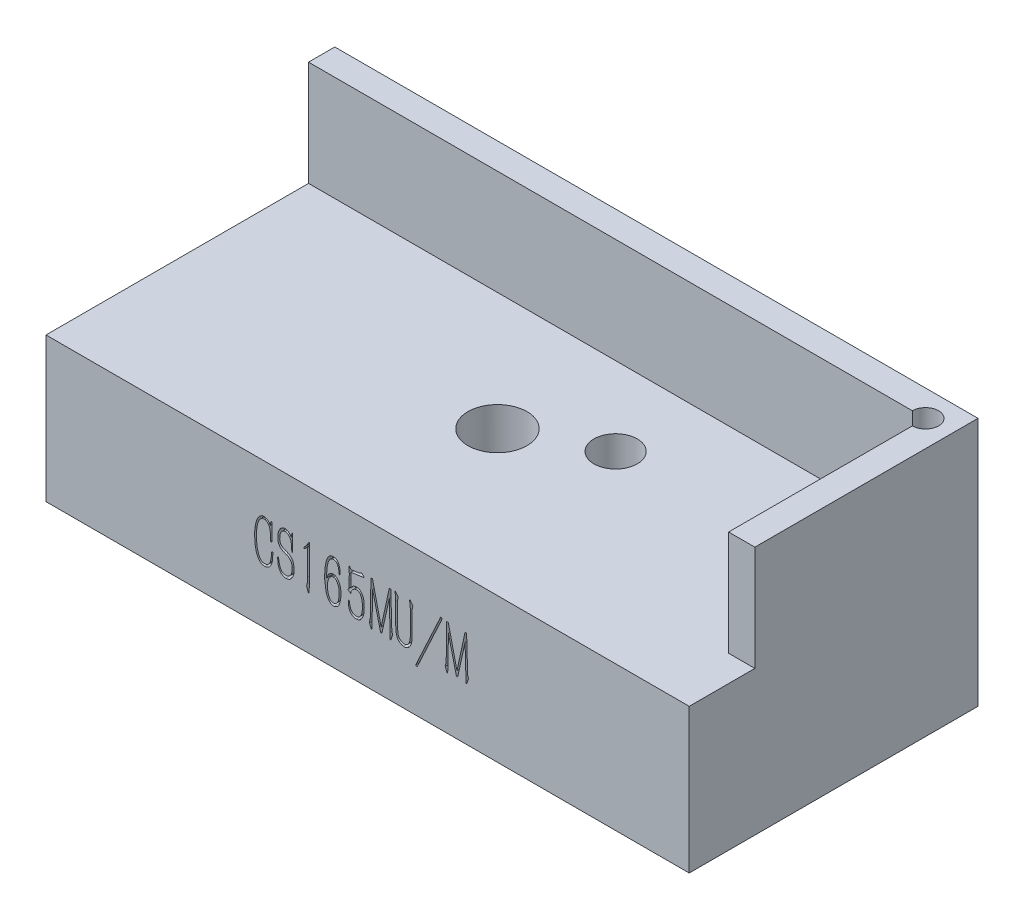
SolidWorks part; units mm, degrees
material "6061 合金"
ref_plane "前视基准面" through (0, 0, 0) normal (0, 0, 1) x (1, 0, 0)
ref_plane "上视基准面" through (0, 0, 0) normal (0, 1, 0) x (1, 0, 0)
ref_plane "右视基准面" through (0, 0, 0) normal (1, 0, 0) x (0, 0, -1)
sketch "草图1" plane through (0, 0, 0) normal (0, 1, 0) x (1, 0, 0)
  line L1 (-23.5, 9) -> (23.5, 9)
  line L2 (-23.5, 9) -> (-23.5, -9)
  line L3 (-23.5, -9) -> (23.5, -9)
  line L4 (23.5, 9) -> (23.5, -9)
  line L5 (-23.5, 9) -> (23.5, -9) construction
  line L6 (-23.5, -9) -> (23.5, 9) construction
  point P0 (0, 0)
  dimension "D1" = 47
  dimension "D2" = 18
extrude "凸台-拉伸1" add sketch "草图1" along normal blind 6
sketch "草图2" plane through (0, 6, 0) normal (0, 1, 0) x (1, 0, 0)
  line L1 (23.5, 9) -> (-23.5, 9) construction
  line L3 (23.5, 9) -> (-23.5, 9)
  line L12 (-23.5, -9) -> (23.5, -9) construction
  line L13 (-23.5, -9) -> (23.5, -9)
  line L19 (23.5, -9) -> (23.5, 9) construction
  line L20 (23.5, -9) -> (23.5, 9)
  line L21 (-23.5, -11) -> (25.5, -11)
  line L22 (25.5, -11) -> (25.5, 11)
  line L23 (25.5, 11) -> (-23.5, 11)
  line L24 (-23.5, -11) -> (-23.5, -9)
  line L25 (-23.5, 9) -> (-23.5, 11)
  dimension "D1" = 2
extrude "凸台-拉伸2" add sketch "草图2" along normal blind 8 and the other way through all
sketch "草图15" plane through (0, 0, 10) normal (0, 1, 0) x (1, 0, 0)
  line L4 (-23.5, -1) -> (25.5, -1)
  line L5 (-23.5, 21) -> (-23.5, -1)
  line L6 (25.5, 21) -> (-23.5, 21)
  line L7 (25.5, -1) -> (25.5, 21)
  line L12 (-23.5, -1) -> (25.5, -1)
  line L13 (-23.5, 21) -> (-23.5, -1)
  line L14 (25.5, 21) -> (-23.5, 21)
  line L15 (25.5, -1) -> (25.5, 21)
  dimension "D1" = 0
extrude "凸台-拉伸3" add sketch "草图15" against normal blind 5
sketch "草图12" plane through (-23.5, 0, 0) normal (-1, 0, 0) x (0, 0, 1)
  line L5 (9, 6) -> (11, 6)
  line L6 (9, 6) -> (9, 14)
  line L7 (9, 14) -> (11, 14)
  line L8 (11, 6) -> (11, 14)
extrude "切除-拉伸5" cut sketch "草图12" against normal offset from surface (37 mm away) 10 up to face at (23.5, 10, 0)
sketch "草图19" plane through (0, 0, 9) normal (0, 0, -1) x (-1, 0, 0)
  line L4 (-23.5, 6) -> (-13.5, 6)
  line L5 (-13.5, 6) -> (-13.5, 14)
  line L6 (-13.5, 14) -> (-23.5, 14)
  line L7 (-23.5, 14) -> (-23.5, 6)
  line L8 (-23.5, 6) -> (-13.5, 6)
  line L10 (-13.5, 14) -> (-23.5, 14)
  line L11 (-23.5, 14) -> (-23.5, 6)
  line L15 (-13.5, 6) -> (-13.5, 14)
  dimension "D1" = 0
extrude "凸台-拉伸4" add sketch "草图19" along normal blind 3
sketch "草图13" plane through (0, 14, 0) normal (0, 1, 0) x (1, 0, 0)
  circle A0 centre (23.5, 9) radius 1
extrude "切除-拉伸6" cut sketch "草图13" against normal up to surface (8 mm away) up to face at (4.5, 6, 2.6667)
sketch "草图5" plane through (0, -5, 0) normal (0, -1, 0) x (1, 0, 0)
  line L1 (-6.622, 9.4855) -> (18.378, 9.4855)
  line L2 (-6.622, 9.4855) -> (-6.622, -15.5145)
  line L3 (-6.622, -15.5145) -> (18.378, -15.5145)
  line L4 (18.378, 9.4855) -> (18.378, -15.5145)
  line L5 (-6.622, 9.4855) -> (18.378, -15.5145) construction
  line L6 (-6.622, -15.5145) -> (18.378, 9.4855) construction
  circle A0 centre (5.878, -3.0145) radius 2.3876 construction
  circle A1 centre (5.878, -3.0145) radius 2.3876 construction
  dimension "D1" = 25
  dimension "D2" = 25
extrude "切除-拉伸1" cut sketch "草图5" along normal up to surface (2.844 mm away)
sketch "草图3" plane through (0, -5, 0) normal (0, 1, 0) x (1, 0, 0)
  line L0 (-0.122, 9) -> (-0.122, 0.0145) construction
  line L1 (23.5, -6) -> (23.5, 8) construction
  line L3 (22.5, 9) -> (-23.5, 9) construction
  line L5 (-0.122, 0.0145) -> (23.5, 0.0145) construction
  circle A0 centre (-0.122, 0.0145) radius 1.3881
  circle A1 centre (-0.122, 0.0145) radius 2.5 construction
hole_wizard "打孔尺寸(%根据)内六角圆柱头螺钉的类型2" positions "3D草图1" profile "草图4" counterbore size "M4" standard "GB" end condition through all
sketch3d "3D草图1"
  point P0 (-0.122, -5, -0.0145)
sketch "草图4" plane through (-0.122, -5, -0.0145) normal (1, 0, 0) x (0, 0, -1)
  line L0 (0, 0) -> (0, 19)
  line L1 (0, 19) -> (2.25, 19)
  line L3 (2.25, 19) -> (2.25, 4.6)
  line L4 (2.25, 4.6) -> (4, 4.6)
  line L5 (4, 4.6) -> (4, 0)
  line L7 (4, 0) -> (0, 0)
  line L11 (0, -6.35) -> (0, 107.95) construction
  dimension "通孔孔直径" = 4.5
  dimension "通孔孔深度" = 19
  dimension "柱形沉头孔直径" = 8
  dimension "柱形沉头孔深度" = 4.6
sketch "草图6" plane through (0, -2.156, 0) normal (0, -1, 0) x (1, 0, 0)
  circle A2 centre (5.878, -3.0145) radius 5
  circle A4 centre (5.878, -3.0145) radius 2.3876 construction
hole_wizard "M4 螺纹孔4" positions "3D草图2" profile "草图20" tap size "M4" standard "GB" end condition through all
sketch3d "3D草图2"
  point P0 (5.878, -2.156, -3.0145)
sketch "草图20" plane through (5.878, -2.156, -3.0145) normal (1, 0, 0) x (0, 0, -1)
  line L0 (0, 0) -> (0, 16.156)
  line L1 (0, 16.156) -> (1.65, 16.156)
  line L2 (1.65, 16.156) -> (1.65, 0)
  line L5 (1.65, 0) -> (0, 0)
  line L11 (0, -6.35) -> (0, 107.95) construction
  dimension "通孔螺纹孔钻头直径" = 3.3
  dimension "通孔螺纹孔钻头深度" = 16.156
cosmetic thread "孔螺蚊线6" parameters "D2"=4
sketch "草图17" plane through (18.378, 0, 0) normal (-1, 0, 0) x (0, 0, 1)
  line L4 (-11, -5) -> (9.4855, -5)
  line L5 (9.4855, -5) -> (9.4855, -2.156)
  line L6 (9.4855, -2.156) -> (-11, -2.156)
  line L7 (-11, -2.156) -> (-11, -5)
  line L10 (9.4855, -2.156) -> (-11, -2.156)
  line L14 (-11, -2.156) -> (-11, -5)
  line L15 (-11, -5) -> (9.4855, -5)
  line L16 (9.4855, -5) -> (9.4855, -2.156)
  dimension "D1" = 0
extrude "切除-拉伸8" cut sketch "草图17" against normal blind 1
sketch "草图18" plane through (0, -5, 0) normal (0, -1, 0) x (-1, 0, 0)
  line L0 (6.622, -9.4855) -> (6.622, 11) construction
  line L1 (-19.378, -9.4855) -> (6.622, -9.4855) construction
  circle A0 centre (6.622, -9.4855) radius 1
extrude "切除-拉伸9" cut sketch "草图18" against normal up to surface (2.844 mm away)
fillet "圆角1" radius 1 1 edges at (19.378, -3.578, 9.4855)
sketch "草图21" plane through (0, 0, 11) normal (0, 0, 1) x (1, 0, 0)
  text T0 "CS165MU/M"
extrude "切除-拉伸10" cut sketch "草图21" against normal blind 0.5
sketch "草图22" plane through (13.5, 0, 0) normal (-1, 0, 0) x (0, 0, 1)
  line L4 (11, 14) -> (6, 14)
  line L5 (6, 14) -> (6, 6)
  line L6 (6, 6) -> (11, 6)
  line L7 (11, 6) -> (11, 14)
  line L8 (11, 14) -> (6, 14)
  line L9 (6, 14) -> (6, 6)
  line L10 (6, 6) -> (11, 6)
  line L11 (11, 6) -> (11, 14)
  dimension "D1" = 0
extrude "切除-拉伸11" cut sketch "草图22" against normal through all
